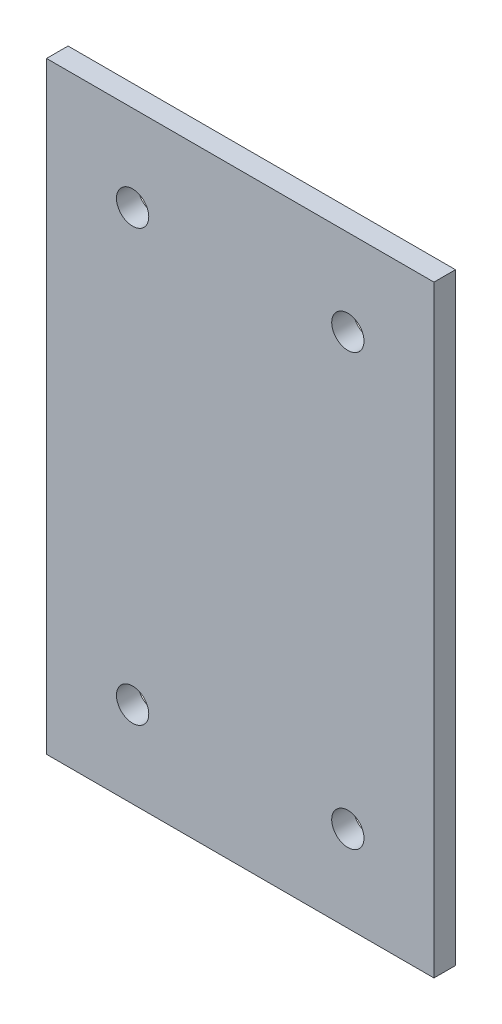
SolidWorks part; units mm, degrees
ref_plane "Спереди" through (0, 0, 0) normal (0, 0, 1) x (1, 0, 0)
ref_plane "Сверху" through (0, 0, 0) normal (0, 1, 0) x (1, 0, 0)
ref_plane "Справа" through (0, 0, 0) normal (1, 0, 0) x (0, 0, -1)
sketch "Эскиз1" plane through (0, 0, 0) normal (0, 0, 1) x (1, 0, 0)
  line L1 (0, 0) -> (36, 0)
  line L2 (0, 0) -> (0, 56)
  line L3 (0, 56) -> (36, 56)
  line L4 (36, 0) -> (36, 56)
  circle A0 centre (8, 8) radius 1.5
  circle A1 centre (28, 8) radius 1.5
  circle A2 centre (28, 48) radius 1.5
  circle A3 centre (8, 48) radius 1.5
  dimension "D3" = 3
  dimension "D2" = 20
  dimension "D4" = 8
  dimension "D5" = 8
  dimension "D8" = 8
  dimension "D9" = 8
  dimension "D10" = 8
  dimension "D11" = 40
  dimension "D7" = 2
  dimension "D6" = 2
extrude "Бобышка-Вытянуть1" add sketch "Эскиз1" along normal blind 2
